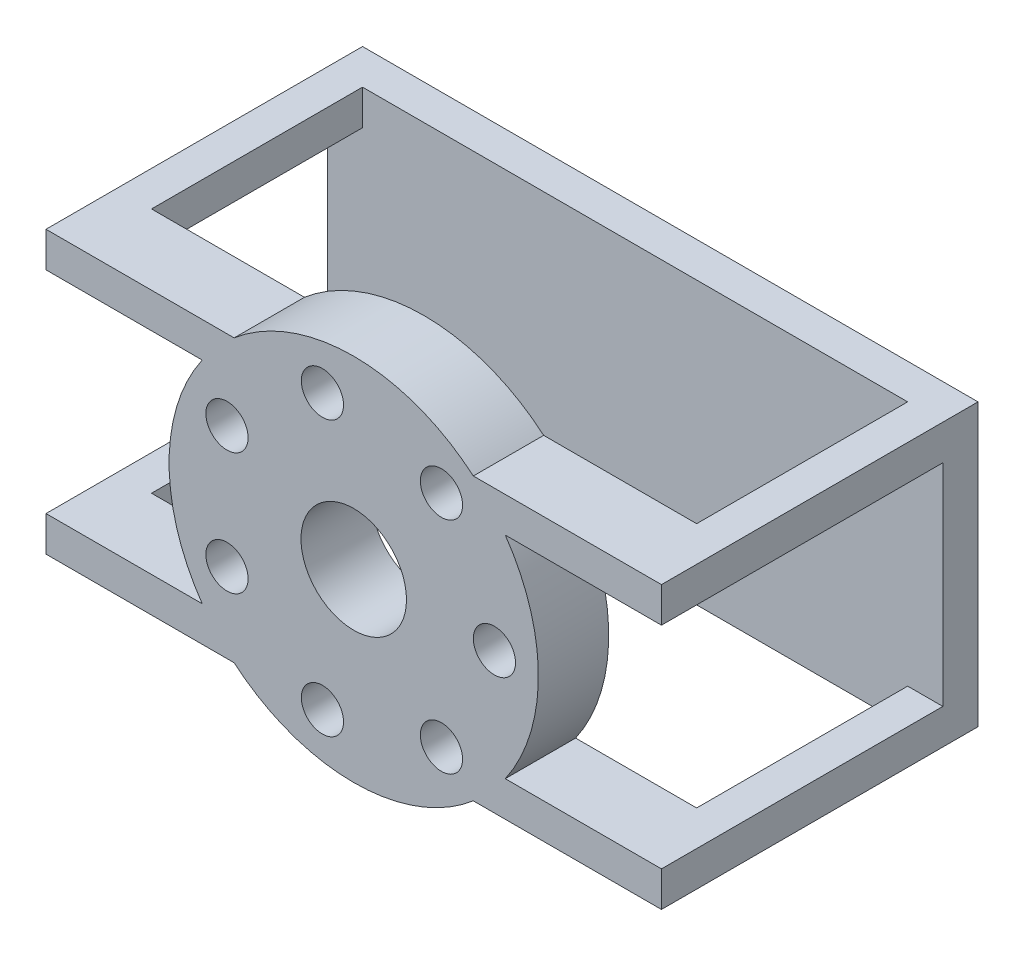
SolidWorks part; units mm, degrees
ref_plane "Front Plane" through (0, 0, 0) normal (0, 0, 1) x (1, 0, 0)
ref_plane "Top Plane" through (0, 0, 0) normal (0, 1, 0) x (1, 0, 0)
ref_plane "Right Plane" through (0, 0, 0) normal (1, 0, 0) x (0, 0, -1)
sketch "Sketch2" plane through (0, 0, 0) normal (0, 1, 0) x (1, 0, 0)
  line L1 (87.5, 90) -> (-87.5, 90)
  line L2 (87.5, 90) -> (87.5, 0)
  line L3 (87.5, 0) -> (-87.5, 0)
  line L4 (-87.5, 90) -> (-87.5, 0)
  line L5 (87.5, 90) -> (-87.5, 0) construction
  line L6 (87.5, 0) -> (-87.5, 90) construction
  line L8 (77.5, 80) -> (-77.5, 80)
  line L9 (77.5, 80) -> (77.5, 20)
  line L10 (77.5, 20) -> (-77.5, 20)
  line L11 (-77.5, 80) -> (-77.5, 20)
  point P0 (0, 45)
  point P7 (0, 45)
  point P12 (0, 0)
  dimension "D1" = 10
  dimension "D2" = 175
  dimension "D3" = 10
  dimension "D4" = 10
  dimension "D5" = 90
  dimension "D6" = 20
extrude "Boss-Extrude3" add sketch "Sketch2" along normal mid plane 105 contours L11 L10 L9 L8
sketch "Sketch3" plane through (0, 0, 0) normal (0, 0, 1) x (1, 0, 0)
  line L0 (-87.5, 52.5) -> (87.5, 52.5) construction
  line L1 (-87.5, 40) -> (-34.0037, 40)
  line L2 (-87.5, 52.5) -> (-87.5, -52.5) construction
  line L3 (0, 0) -> (87.5, 0) construction
  line L4 (87.5, 52.5) -> (87.5, -52.5) construction
  line L5 (0, 0) -> (0, 52.5) construction
  line L6 (-87.5, 30) -> (-43.0842, 30)
  line L7 (87.5, 30) -> (43.0842, 30)
  line L8 (87.5, 40) -> (34.0037, 40)
  line L9 (87.5, -30) -> (43.0842, -30)
  line L10 (87.5, -40) -> (34.0037, -40)
  line L11 (-87.5, -30) -> (-43.0842, -30)
  line L12 (-87.5, -40) -> (-34.0037, -40)
  line L17 (-87.5, -52.5) -> (87.5, -52.5)
  line L18 (87.5, -52.5) -> (87.5, 52.5)
  line L19 (87.5, 52.5) -> (-87.5, 52.5)
  line L20 (-87.5, 52.5) -> (-87.5, -52.5)
  line L21 (-87.5, -52.5) -> (87.5, -52.5)
  line L22 (87.5, -52.5) -> (87.5, 52.5)
  line L23 (87.5, 52.5) -> (-87.5, 52.5)
  line L24 (-87.5, 52.5) -> (-87.5, -52.5)
  circle A0 centre (0, 0) radius 52.5
  circle A1 centre (0, 0) radius 40 construction
  circle A2 centre (40, 0) radius 6
  circle A3 centre (24.9396, -31.2733) radius 6
  circle A4 centre (-8.9008, -38.9971) radius 6
  circle A5 centre (-36.0388, -17.3553) radius 6
  circle A6 centre (-36.0388, 17.3553) radius 6
  circle A7 centre (-8.9008, 38.9971) radius 6
  circle A8 centre (24.9396, 31.2733) radius 6
  circle A9 centre (0, 0) radius 15
  point P48 (0, 0)
  line M11 (-87.5, -52.5) -> (87.5, -52.5)
  line M12 (87.5, -52.5) -> (87.5, 52.5)
  line M13 (87.5, 52.5) -> (-87.5, 52.5)
  line M14 (-87.5, 52.5) -> (-87.5, -52.5)
  dimension "D4" = 80
  dimension "D5" = 12
  dimension "D7" = 30
  dimension "D1" = 40
  dimension "D2" = 30
  dimension "D3" = 0
  dimension "D6" = 7
extrude "Cut-Extrude1" cut sketch "Sketch3" against normal blind 80 contours A0 L23 L1 M14 | A0 L8 M12 M13 | A0 L12 M14 M11 | A0 L21 L10 M12 | A0 L9 L7 M12 | A0 L6 L11 M14 | A7 | A8 | A6 | A2 | A5 | A4 | A3 | A9
sketch "Sketch4" plane through (0, 0, -80) normal (0, 0, 1) x (1, 0, 0)
  line L0 (87.5, 52.5) -> (-87.5, 52.5) construction
  line L1 (87.5, 52.5) -> (-87.5, 52.5)
  line L2 (87.5, 40) -> (87.5, 52.5) construction
  line L3 (-87.5, 52.5) -> (-87.5, 40) construction
  line L4 (87.5, 40) -> (87.5, 52.5)
  line L5 (-87.5, 52.5) -> (-87.5, 40)
  line L6 (-87.5, 40) -> (87.5, 40)
  line L7 (0, 0) -> (-98.9779, 0) construction
  line L8 (-87.5, -40) -> (87.5, -40)
  line L9 (-87.5, -52.5) -> (-87.5, -40)
  line L10 (87.5, -40) -> (87.5, -52.5)
  line L11 (87.5, -52.5) -> (-87.5, -52.5)
extrude "Cut-Extrude2" cut sketch "Sketch4" against normal up to surface (10 mm away) up to face at (0, 0, -90)
